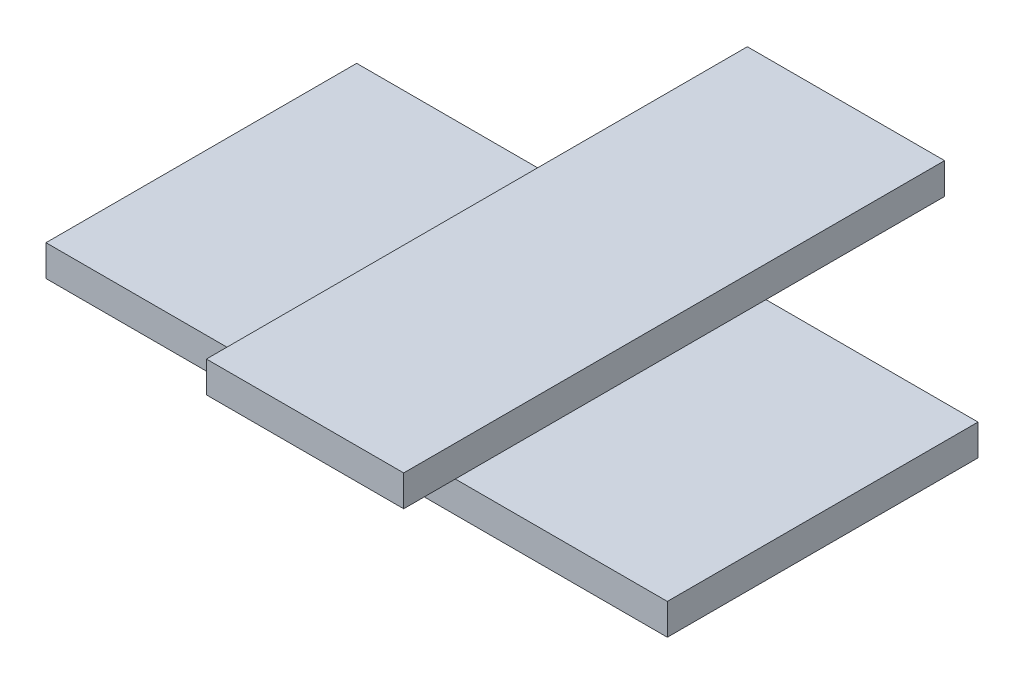
SolidWorks part; units mm, degrees
ref_plane "Front Plane" through (0, 0, 0) normal (0, 0, 1) x (1, 0, 0)
ref_plane "Top Plane" through (0, 0, 0) normal (0, 1, 0) x (1, 0, 0)
ref_plane "Right Plane" through (0, 0, 0) normal (1, 0, 0) x (0, 0, -1)
sketch "Sketch1" plane through (0, 0, 0) normal (0, 1, 0) x (1, 0, 0)
  line L1 (0, 0) -> (200, 0)
  line L2 (0, 0) -> (0, 100)
  line L3 (0, 100) -> (200, 100)
  line L4 (200, 0) -> (200, 100)
  dimension "D1" = 200
  dimension "D2" = 100
extrude "Boss-Extrude1" add sketch "Sketch1" along normal blind 10
sketch "Sketch2" plane through (0, 10, 0) normal (0, 1, 0) x (1, 0, 0)
  line L0 (100, 157.5058) -> (100, -16.6117) construction
  line L1 (68.25, 157.5058) -> (131.75, 157.5058)
  line L2 (68.25, 157.5058) -> (68.25, -16.6117)
  line L3 (68.25, -16.6117) -> (131.75, -16.6117)
  line L4 (131.75, 157.5058) -> (131.75, -16.6117)
  line L5 (100, 100) -> (100, 0) construction
  line L6 (200, 100) -> (0, 100) construction
  line L7 (0, 0) -> (200, 0) construction
  dimension "D1" = 174.1175
  dimension "D2" = 63.5
extrude "Boss-Extrude2" add sketch "Sketch2" along normal blind 10
